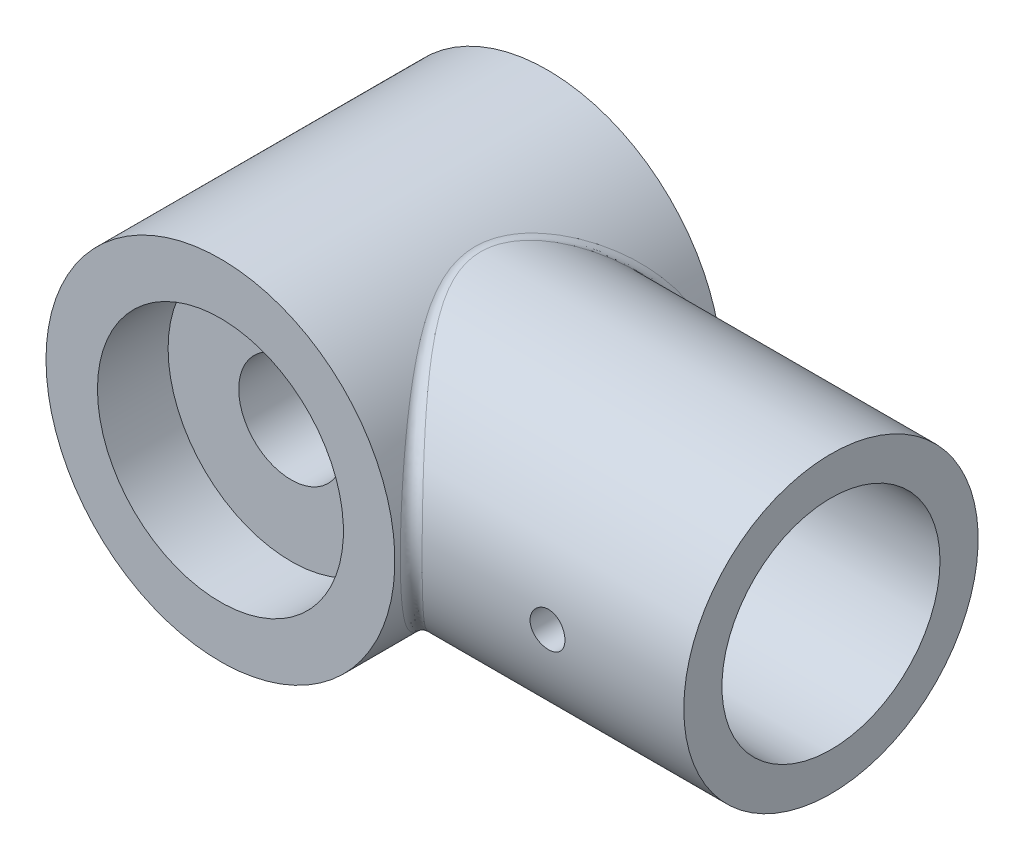
SolidWorks part; units mm, degrees
ref_plane "Front Plane" through (0, 0, 0) normal (0, 0, 1) x (1, 0, 0)
ref_plane "Top Plane" through (0, 0, 0) normal (0, 1, 0) x (1, 0, 0)
ref_plane "Right Plane" through (0, 0, 0) normal (1, 0, 0) x (0, 0, -1)
ref_plane "Plane1" through (0, 0, 0) normal (0, -1, 0) x (1, 0, 0)
sketch "Sketch1" plane through (0, 0, 0) normal (0, -1, 0) x (1, 0, 0)
  line L0 (16, 30) -> (0, 30)
  line L1 (0, 30) -> (0, 0)
  line L2 (0, 0) -> (16, 0)
  line L3 (16, 0) -> (16, 30)
  line L4 (0, 30) -> (0, 0) construction
revolve "Revolve1" add sketch "Sketch1" angle 360 about L4
ref_plane "Plane2" through (0, -4.2549, 1.3238) normal (0, 0.9549, -0.2971) x (-1, 0, 0)
sketch "Sketch2" plane through (0, -4.2549, 1.3238) normal (0, 0.9549, -0.2971) x (-1, 0, 0)
  line L0 (-8.5878, 14.3228) -> (-8.5878, 27.8228)
  line L1 (-8.5878, 27.8228) -> (-41, 27.8228)
  line L2 (-41, 27.8228) -> (-41, 14.3228)
  line L3 (-41, 14.3228) -> (-8.5878, 14.3228)
  line L4 (-41, 14.3228) -> (-8.5878, 14.3228) construction
revolve "Revolve2" add sketch "Sketch2" angle 360 about L4
sketch "Sketch3" plane through (0, 0, 0) normal (0, -1, 0) x (1, 0, 0)
  line L0 (11.28, 30) -> (0, 30)
  line L1 (0, 30) -> (0, 0)
  line L2 (0, 0) -> (11.28, 0)
  line L3 (11.28, 0) -> (11.28, 6.48)
  line L4 (11.28, 6.48) -> (4.8, 6.48)
  line L5 (4.8, 6.48) -> (4.8, 23.52)
  line L6 (4.8, 23.52) -> (11.28, 23.52)
  line L7 (11.28, 23.52) -> (11.28, 30)
  line L8 (0, 30) -> (0, 0) construction
  dimension "D1" = 11.28
  dimension "D2" = 6.48
  dimension "D3" = 4.8
revolve "Cut-Revolve1" cut sketch "Sketch3" angle 360 about L8
hole_wizard "Ø20.0 (20) Diameter Hole1" positions "Sketch5" profile "Sketch4" hole size "Ø20.0" standard "ANSI Metric"
sketch "Sketch5" plane through (41, 0, 0) normal (1, 0, 0) x (0, 0, -1)
  point P0 (-15, 0)
sketch "Sketch4" plane through (41, 0, 15) normal (0, 1, 0) x (0, 0, -1)
  line L0 (0, 0) -> (0, 25)
  line L1 (0, 25) -> (10, 25)
  line L2 (10, 25) -> (10, 0)
  line L5 (10, 0) -> (0, 0)
  line L10 (0, 25) -> (-10, 25) construction
  line L11 (0, -6.35) -> (0, 107.95) construction
  dimension "Hole Dia." = 20
  dimension "Hole Depth" = 25
  dimension "Drill Angle" = 180
ref_plane "Plane3" through (0, 0, 5.202) normal (0, 0, 1) x (1, 0, 0)
hole_wizard "Ø4.0 (3.2) Diameter Hole1" positions "Sketch7" profile "Sketch6" hole size "Ø4.0" standard "ANSI Metric"
sketch "Sketch7" plane through (0, 0, 5.202) normal (0, 0, 1) x (1, 0, 0)
  point P0 (28.5, 0)
sketch "Sketch6" plane through (28.5, 0, 5.202) normal (1, 0, 0) x (0, -1, 0)
  line L0 (0, 0) -> (0, 5.202)
  line L1 (0, 5.202) -> (1.6, 5.202)
  line L2 (1.6, 5.202) -> (1.6, 0)
  line L5 (1.6, 0) -> (0, 0)
  line L11 (0, -6.35) -> (0, 107.95) construction
  dimension "Thru Hole Dia." = 3.2
  dimension "Thru Hole Depth" = 5.202
fillet "Fillet1" radius 1 1 edges at (15.568, 3.6927, 2.0149)
scale "Scale1" scale about centroid uniform scaling yes scale factor 1.25
sketch "Sketch8" plane through (0, 0, 0) normal (0, 0, 1) x (1, 0, 0)
  circle A0 centre (33.6655, 0) radius 2
extrude "Cut-Extrude1" cut sketch "Sketch8" against normal through all both and the other way through all
